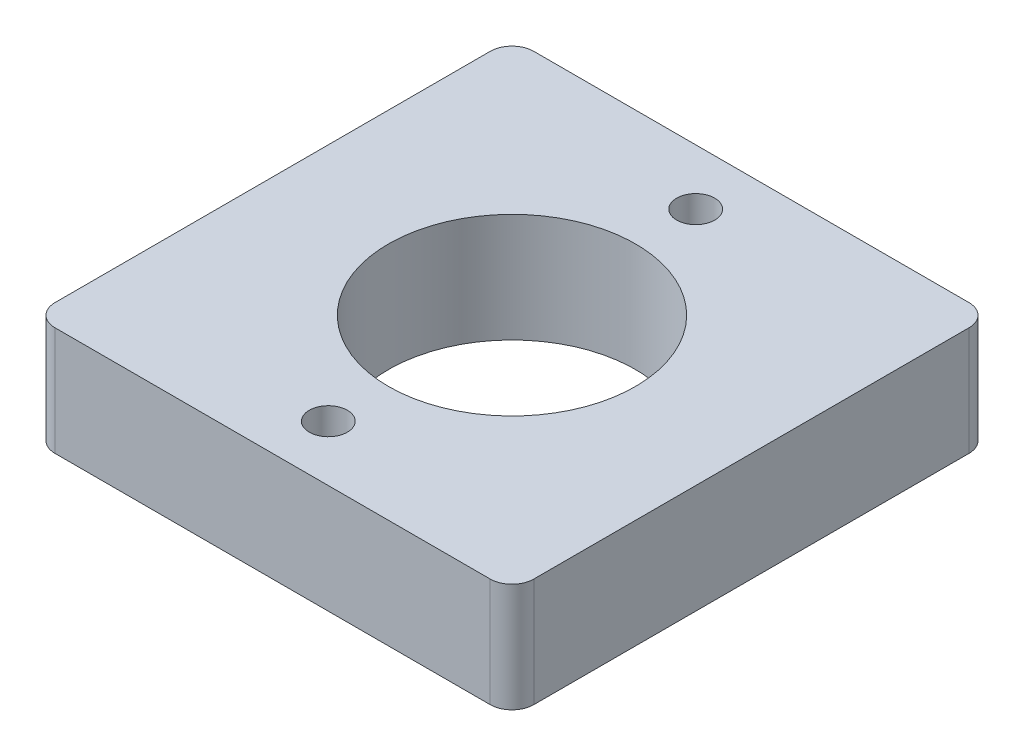
SolidWorks part; units mm, degrees
ref_plane "Alzado" through (0, 0, 0) normal (0, 0, 1) x (1, 0, 0)
ref_plane "Planta" through (0, 0, 0) normal (0, 1, 0) x (1, 0, 0)
ref_plane "Vista lateral" through (0, 0, 0) normal (1, 0, 0) x (0, 0, -1)
sketch "Croquis1" plane through (0, 0, 0) normal (0, 1, 0) x (1, 0, 0)
  line L1 (-22, -22) -> (22, -22)
  line L2 (-22, -22) -> (-22, 22)
  line L3 (-22, 22) -> (22, 22)
  line L4 (22, -22) -> (22, 22)
  line L5 (-22, -22) -> (22, 22) construction
  line L6 (-22, 22) -> (22, -22) construction
  circle A0 centre (0, 0) radius 11.35
  point P0 (0, 0)
  dimension "D3" = 22.7
  dimension "D1" = 44
  dimension "D2" = 44
extrude "Saliente-Extruir1" add sketch "Croquis1" along normal blind 10
sketch "Croquis2" plane through (0, 10, 0) normal (0, 1, 0) x (1, 0, 0)
  line L0 (-22, 22) -> (-22, -22) construction
  line L1 (22, -11.75) -> (-22, -11.75) construction
  line L2 (22, -11.75) -> (22, 11.75) construction
  line L3 (22, 11.75) -> (-22, 11.75) construction
  line L4 (-22, -11.75) -> (-22, 11.75) construction
  line L5 (22, -11.75) -> (-22, 11.75) construction
  line L6 (22, 11.75) -> (-22, -11.75) construction
  line L7 (-22, 16.88) -> (22, 16.88) construction
  line L8 (22, -22) -> (22, 22) construction
  line L9 (0, 22) -> (0, -22) construction
  line L10 (22, 22) -> (-22, 22) construction
  line L11 (-22, -22) -> (22, -22) construction
  line L12 (-22, -16.88) -> (22, -16.88) construction
  circle A0 centre (0, 16.88) radius 1.75
  circle A1 centre (0, -16.88) radius 1.75
  point P0 (0, 0)
  point P18 (0, 16.88)
  point P19 (0, -16.88)
  dimension "D4" = 3.5
  dimension "D5" = 3.5
  dimension "D1" = 23.5
  dimension "D2" = 5.13
  dimension "D3" = 5.13
extrude "Cortar-Extruir1" cut sketch "Croquis2" against normal through all
fillet "Redondeo1" radius 2 4 edges at (22, 5, -22) (22, 5, 22) (-22, 5, 22) (-22, 5, -22)
